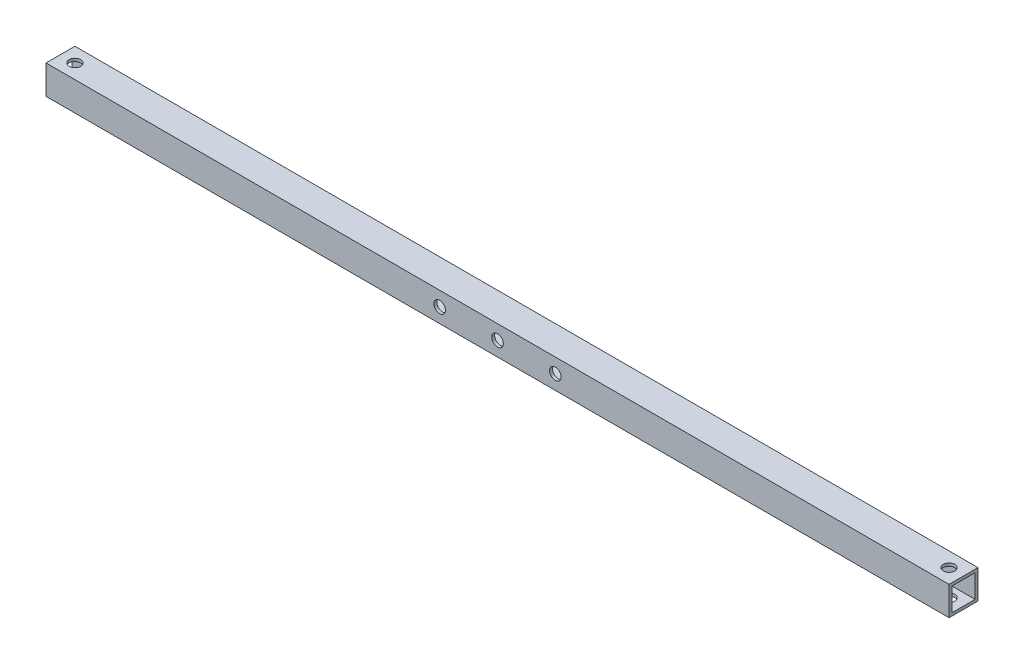
SolidWorks part; units mm, degrees
material "5052-H34"
ref_plane "正面" through (0, 0, 0) normal (0, 0, 1) x (1, 0, 0)
ref_plane "平面" through (0, 0, 0) normal (0, 1, 0) x (1, 0, 0)
ref_plane "右側面" through (0, 0, 0) normal (1, 0, 0) x (0, 0, -1)
sketch "ｽｹｯﾁ1" plane through (0, 0, 0) normal (1, 0, 0) x (0, 0, -1)
  line L1 (-5, 5) -> (5, 5)
  line L2 (-5, 5) -> (-5, -5)
  line L3 (-5, -5) -> (5, -5)
  line L4 (5, 5) -> (5, -5)
  line L5 (-5, 5) -> (5, -5) construction
  line L6 (-5, -5) -> (5, 5) construction
  point P0 (0, 0)
  dimension "D1" = 10
  dimension "D2" = 10
extrude "押し出し-薄板1" add sketch "ｽｹｯﾁ1" along normal blind 312 thin
sketch "ｽｹｯﾁ2" plane through (0, 5, 0) normal (0, 1, 0) x (1, 0, 0)
  line L0 (156, 5) -> (156, -5) construction
  line L1 (312, 5) -> (0, 5) construction
  line L2 (312, -5) -> (0, -5) construction
  line L3 (0, 0) -> (5, 0) construction
  line L4 (312, 0) -> (307, 0) construction
  circle A0 centre (5, 0) radius 2
  circle A1 centre (307, 0) radius 2
  dimension "D1" = 4
  dimension "D2" = 5
extrude "ｶｯﾄ - 押し出し1" cut sketch "ｽｹｯﾁ2" against normal through all
sketch "ｽｹｯﾁ3" plane through (0, 0, 5) normal (0, 0, 1) x (1, 0, 0)
  line L0 (156, 5) -> (156, -5) construction
  line L1 (312, 5) -> (0, 5) construction
  line L2 (312, -5) -> (0, -5) construction
  line L3 (136, 0) -> (176, 0) construction
  circle A0 centre (136, 0) radius 2
  circle A1 centre (156, 0) radius 2
  circle A2 centre (176, 0) radius 2
  point P13 (156, 0)
  dimension "D1" = 4
  dimension "D2" = 40
extrude "ｶｯﾄ - 押し出し2" cut sketch "ｽｹｯﾁ3" against normal through all
